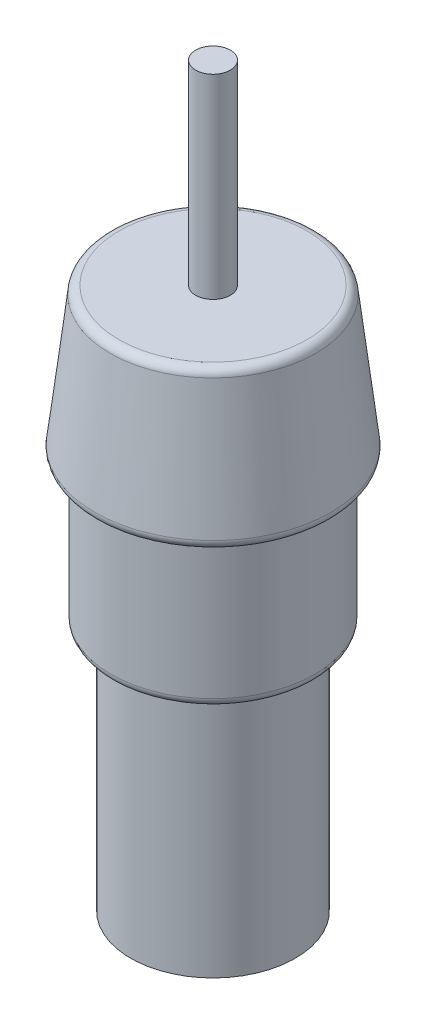
SolidWorks part; units mm, degrees
material "PPS"
ref_plane "Front Plane" through (0, 0, 0) normal (0, 0, 1) x (1, 0, 0)
ref_plane "Top Plane" through (0, 0, 0) normal (0, 1, 0) x (1, 0, 0)
ref_plane "Right Plane" through (0, 0, 0) normal (1, 0, 0) x (0, 0, -1)
sketch "Sketch1" plane through (0, 0, 0) normal (0, 1, 0) x (1, 0, 0)
  circle A0 centre (-72.2489, 15.9323) radius 19
  dimension "D1" = 38
extrude "Boss-Extrude1" add sketch "Sketch1" along normal blind 57
sketch "Sketch2" plane through (0, 57, 0) normal (0, 1, 0) x (1, 0, 0)
  circle A0 centre (-72.2489, 15.9323) radius 23.5
  dimension "D1" = 47
extrude "Boss-Extrude2" add sketch "Sketch2" along normal blind 34
sketch "Sketch3" plane through (0, 91, 0) normal (0, 1, 0) x (1, 0, 0)
  circle A0 centre (-72.2489, 15.9323) radius 27.5
  circle A1 centre (-72.2489, 15.9323) radius 23.5 construction
  dimension "D1" = 4
ref_plane "Plane1" through (0, 125, 0) normal (0, 1, 0) x (1, 0, 0)
sketch "Sketch4" plane through (0, 125, 0) normal (0, 1, 0) x (1, 0, 0)
  circle A0 centre (-72.2489, 15.9323) radius 23.5
  dimension "D1" = 47
loft "Loft1" add profiles "Sketch3", "Sketch4"
sketch "Sketch5" plane through (0, 125, 0) normal (0, 1, 0) x (1, 0, 0)
  circle A0 centre (-72.2489, 15.9323) radius 4
  dimension "D1" = 8
extrude "Boss-Extrude3" add sketch "Sketch5" along normal blind 45
fillet "Fillet1" radius 2 3 edges at (-72.2489, 57, 7.5677) (-72.2489, 91, 11.5677) (-72.2489, 125, 7.5677)
